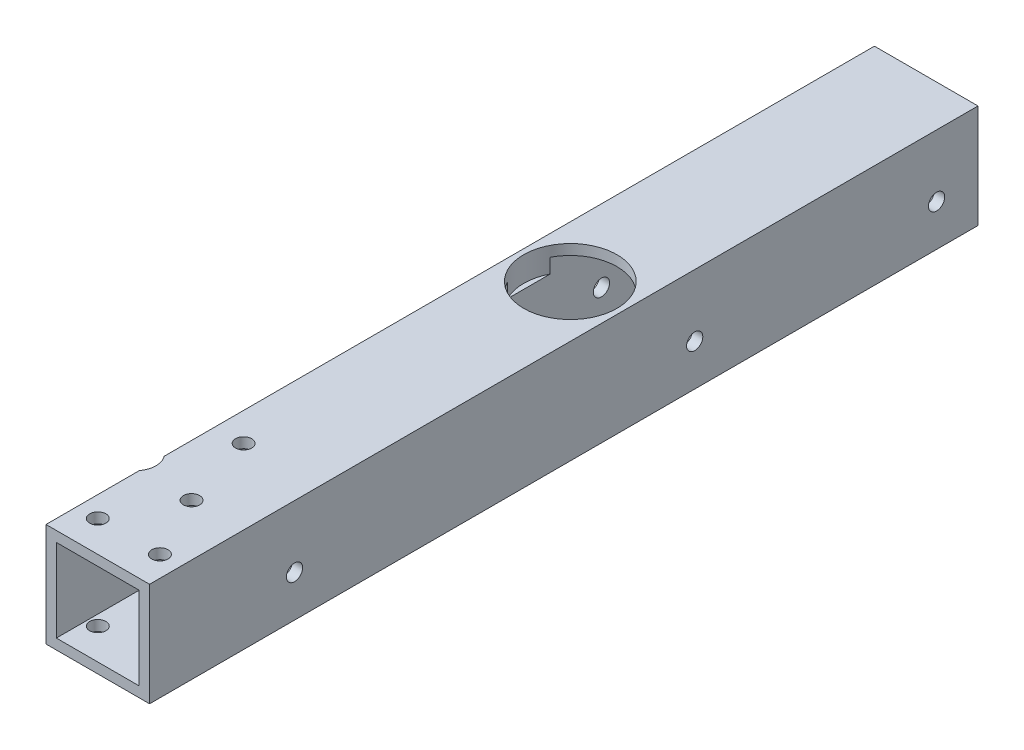
SolidWorks part; units mm, degrees
material "6061 Alloy"
ref_plane "Front Plane" through (0, 0, 0) normal (0, 0, 1) x (1, 0, 0)
ref_plane "Top Plane" through (0, 0, 0) normal (0, 1, 0) x (1, 0, 0)
ref_plane "Right Plane" through (0, 0, 0) normal (1, 0, 0) x (0, 0, -1)
sketch "Sketch1" plane through (0, 0, 0) normal (0, 0, 1) x (1, 0, 0)
  line L0 (-12.7, 12.7) -> (12.7, 12.7)
  line L2 (-15.875, 15.875) -> (15.875, 15.875)
  line L3 (-15.875, 15.875) -> (-15.875, -15.875)
  line L4 (-15.875, -15.875) -> (15.875, -15.875)
  line L5 (15.875, 15.875) -> (15.875, -15.875)
  line L10 (12.7, 12.7) -> (12.7, -12.7)
  line L11 (-12.7, -12.7) -> (12.7, -12.7)
  line L12 (-12.7, 12.7) -> (-12.7, -12.7)
  point P12 (0, 15.875)
  point P14 (15.875, 0)
  dimension "Wall Thickness" = 3.175
  dimension "Outside Width" = 31.75
  dimension "Outside Height" = 31.75
  dimension "Inside Height" = 25.4
  dimension "Inside Width" = 25.4
sketch "Sketch2" plane through (0, 0, 0) normal (1, 0, 0) x (0, 0, -1)
  line L0 (127, 0) -> (-127, 0)
  point P4 (0, 0)
  point P7 (-127, 0)
  point P10 (127, 0)
  dimension "Length" = 254
sketch "Sketch3" plane through (0, 0, 0) normal (0, 0, 1) x (1, 0, 0)
  line L21 (15.875, 15.875) -> (-15.875, 15.875)
  line L22 (15.875, -15.875) -> (15.875, 15.875)
  line L23 (-15.875, -15.875) -> (15.875, -15.875)
  line L24 (-15.875, 15.875) -> (-15.875, -15.875)
  line L25 (15.875, 15.875) -> (-15.875, 15.875)
  line L26 (15.875, -15.875) -> (15.875, 15.875)
  line L27 (-15.875, -15.875) -> (15.875, -15.875)
  line L28 (-15.875, 15.875) -> (-15.875, -15.875)
  line L29 (12.7, 12.7) -> (-12.7, 12.7)
  line L30 (12.7, -12.7) -> (12.7, 12.7)
  line L31 (-12.7, -12.7) -> (12.7, -12.7)
  line L32 (-12.7, 12.7) -> (-12.7, -12.7)
  line L33 (12.7, 12.7) -> (-12.7, 12.7)
  line L34 (12.7, -12.7) -> (12.7, 12.7)
  line L35 (-12.7, -12.7) -> (12.7, -12.7)
  line L36 (-12.7, 12.7) -> (-12.7, -12.7)
  dimension "D1" = 0
  dimension "D2" = 0
extrude "Boss-Extrude1" add sketch "Sketch3" along normal up to vertex (127 mm away) and the other way up to vertex (127 mm away) up to point (0, 0, 127) other way up to point (0, 0, -127)
sketch "Drawing Reference" plane through (0, 0, 0) normal (1, 0, 0) x (0, 0, -1)
  line L0 (-127, 0) -> (127, 0) construction
  line L1 (0, -15.875) -> (0, 15.875) construction
  line L2 (-127, -15.875) -> (127, -15.875) construction
  line L5 (-127, 15.875) -> (127, 15.875) construction
  point P7 (-104.14, 0)
  point P8 (104.14, 0)
  dimension "D1" = 22.86
sketch "Sketch4" plane through (0, 15.875, 0) normal (0, 1, 0) x (1, 0, 0)
  line L0 (0, -127) -> (0, -117.475) construction
  line L1 (15.875, -127) -> (-15.875, -127) construction
  line L2 (0, -117.475) -> (9.525, -117.475) construction
  line L3 (0, -117.475) -> (-9.525, -117.475) construction
  line L4 (0, -117.475) -> (0, 17.8816) construction
  line L5 (0, -117.475) -> (0, -98.2472) construction
  point P5 (-7.1119, -75.1713)
  dimension "D1" = 135.3566
  dimension "D2" = 19.05
  dimension "D3" = 9.525
hole_wizard "#10 Clearance Hole1" positions "Sketch5" profile "Sketch6" hole size "#10" standard "ANSI Inch" end condition through all
sketch "Sketch5" plane through (0, 15.875, 0) normal (0, 1, 0) x (1, 0, 0)
  point P0 (-9.525, -117.475)
  point P3 (9.525, -117.475)
  point P7 (0, -98.2472)
  point P10 (-7.1119, -75.1713)
sketch "Sketch6" plane through (-9.525, 15.875, 117.475) normal (1, 0, 0) x (0, 0, 1)
  line L0 (0, 0) -> (0, 31.75)
  line L1 (0, 31.75) -> (2.4892, 31.75)
  line L2 (2.4892, 31.75) -> (2.4892, 0)
  line L5 (2.4892, 0) -> (0, 0)
  line L11 (0, -6.35) -> (0, 107.95) construction
  dimension "Thru Hole Dia." = 4.9784
  dimension "Thru Hole Depth" = 31.75
sketch "Sketch7" plane through (0, 15.875, 0) normal (0, 1, 0) x (1, 0, 0)
  circle A0 centre (0, 17.8816) radius 14.2875
  dimension "D1" = 28.575
extrude "Cut-Extrude1" cut sketch "Sketch7" against normal blind 7.62
sketch "Sketch8" plane through (0, -15.875, 0) normal (0, -1, 0) x (1, 0, 0)
  circle A0 centre (0, -17.8816) radius 14.2875
  dimension "D1" = 28.575
extrude "Cut-Extrude2" cut sketch "Sketch8" against normal blind 7.62
sketch "Sketch9" plane through (15.875, 0, 0) normal (1, 0, 0) x (0, 0, -1)
  line L0 (-127, -3.175) -> (-82.55, -3.175) construction
  line L2 (-82.55, -3.175) -> (114.3, -3.175) construction
  line L3 (-127, 15.875) -> (-127, -3.175) construction
  line L4 (52.832, -3.175) -> (40.132, -3.175) construction
  line L5 (52.832, 10.4775) -> (52.832, -434.0225) construction
  dimension "D1" = 44.45
  dimension "D2" = 19.05
  dimension "D3" = 12.7
hole_wizard "#10 Clearance Hole2" positions "Sketch10" profile "Sketch11" hole size "#10" standard "ANSI Inch" end condition through all
sketch "Sketch10" plane through (15.875, 0, 0) normal (1, 0, 0) x (0, 0, -1)
  point P0 (-82.55, -3.175)
  point P4 (114.3, -3.175)
  point P8 (40.132, -3.175)
sketch "Sketch11" plane through (15.875, -3.175, 82.55) normal (0, 1, 0) x (0, 0, -1)
  line L0 (0, 0) -> (0, 31.75)
  line L1 (0, 31.75) -> (2.4892, 31.75)
  line L2 (2.4892, 31.75) -> (2.4892, 0)
  line L5 (2.4892, 0) -> (0, 0)
  line L11 (0, -6.35) -> (0, 107.95) construction
  dimension "Thru Hole Dia." = 4.9784
  dimension "Thru Hole Depth" = 31.75
sketch "Sketch12" plane through (0, 15.875, 0) normal (0, 1, 0) x (1, 0, 0)
  line L0 (-20.955, -94.5576) -> (-15.875, -94.5576) construction
  line L1 (-15.875, -127) -> (-15.875, 127) construction
  circle A0 centre (-20.955, -94.5576) radius 6.35
  dimension "D1" = 5.08
extrude "Cut-Extrude3" cut sketch "Sketch12" against normal through all
sketch "Sketch13" plane through (0, -15.875, 0) normal (0, -1, 0) x (1, 0, 0)
  line L0 (0, 0.1524) -> (0, -35.9156) construction
  line L1 (0, -17.8816) -> (3.2229, -17.8816) construction
  point P8 (0, -17.8816)
  dimension "D1" = 36.068
hole_wizard "Tap Drill for #8-32 Tap1" positions "Sketch14" profile "Sketch15" hole size "#8-32" standard "ANSI Inch"
sketch "Sketch14" plane through (0, -15.875, 0) normal (0, -1, 0) x (-1, 0, 0)
  point P2 (0, 35.9156)
  point P5 (0, -0.1524)
sketch "Sketch15" plane through (0, -15.875, -35.9156) normal (1, 0, 0) x (0, 0, -1)
  line L0 (0, 0) -> (0, 6.1178)
  line L1 (0, 6.1178) -> (1.7272, 5.08)
  line L2 (1.7272, 5.08) -> (1.7272, 0)
  line L5 (1.7272, 0) -> (0, 0)
  line L10 (0, 6.1178) -> (-1.7272, 5.08) construction
  line L11 (0, -6.35) -> (0, 107.95) construction
  dimension "Hole Dia." = 3.4544
  dimension "Hole Depth" = 5.08
  dimension "Drill Angle" = 118
equation "\"D1@Drawing Reference\"=\"Outside Width@Sketch1\" * 0.72"
